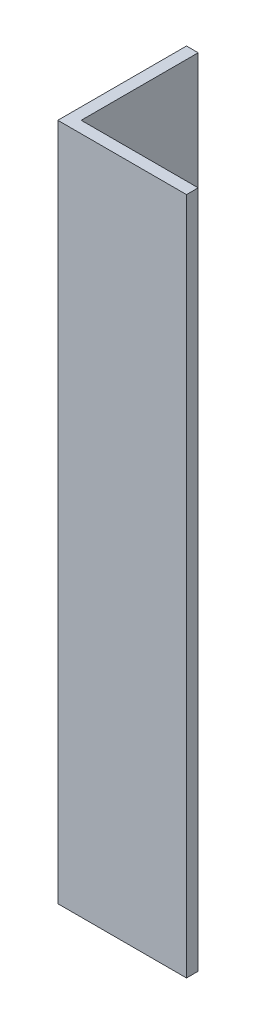
SolidWorks part; units mm, degrees
ref_plane "Спереди" through (0, 0, 0) normal (0, 0, 1) x (1, 0, 0)
ref_plane "Сверху" through (0, 0, 0) normal (0, 1, 0) x (1, 0, 0)
ref_plane "Справа" through (0, 0, 0) normal (1, 0, 0) x (0, 0, -1)
sketch "Эскиз1" plane through (0, 0, 0) normal (0, 1, 0) x (1, 0, 0)
  line L0 (0, -1.0719) -> (0, -21.0719)
  line L1 (0, -21.0719) -> (20, -21.0719)
  line L2 (20, -21.0719) -> (20, -23.0719)
  line L3 (20, -23.0719) -> (-2, -23.0719)
  line L4 (-2, -23.0719) -> (-2, -1.0719)
  line L5 (-2, -1.0719) -> (0, -1.0719)
extrude "Вытянуть1" add sketch "Эскиз1" along normal blind 116
